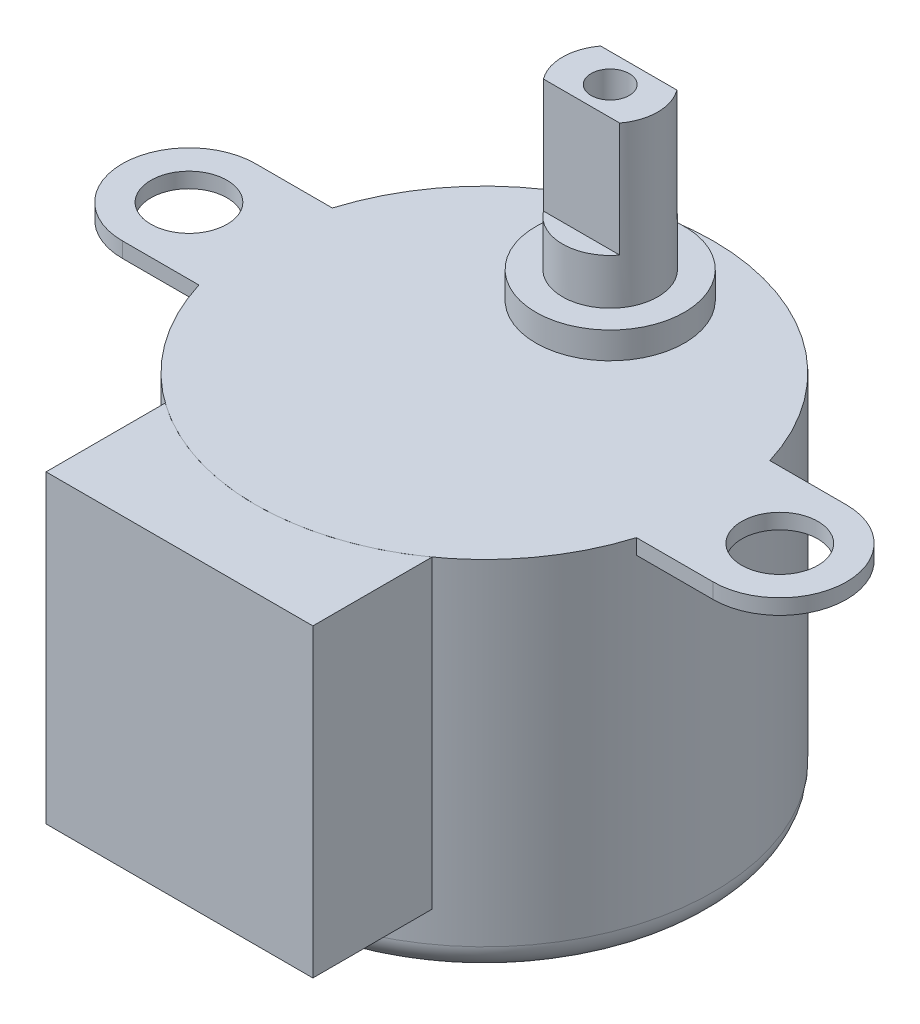
SolidWorks part; units mm, degrees
ref_plane "Front Plane" through (0, 0, 0) normal (0, 0, 1) x (1, 0, 0)
ref_plane "Top Plane" through (0, 0, 0) normal (0, 1, 0) x (1, 0, 0)
ref_plane "Right Plane" through (0, 0, 0) normal (1, 0, 0) x (0, 0, -1)
sketch "Sketch1" plane through (0, 0, 0) normal (0, 1, 0) x (1, 0, 0)
  circle A0 centre (0, 0) radius 12
  dimension "D1" = 24
extrude "Boss-Extrude1" add sketch "Sketch1" along normal blind 19
sketch "Sketch2" plane through (0, 19, 0) normal (0, 1, 0) x (1, 0, 0)
  line L1 (-7, -9.7468) -> (7, -9.7468)
  line L2 (-7, -9.7468) -> (-7, -16)
  line L3 (-7, -16) -> (7, -16)
  line L4 (7, -9.7468) -> (7, -16)
  circle A0 centre (0, 0) radius 12 construction
  point P6 (7.8636, -9.0644)
  circle M5 centre (0, 0) radius 12
  dimension "D1" = 16
  dimension "D2" = 14
extrude "Boss-Extrude2" add sketch "Sketch2" against normal blind 16 separate body contours L4 L2 L3 M5
sketch "Sketch3" plane through (0, 19, 0) normal (0, 1, 0) x (1, 0, 0)
  line L1 (-15.5, 3.5) -> (15.5, 3.5)
  line L2 (-15.5, 3.5) -> (-15.5, -3.5)
  line L3 (-15.5, -3.5) -> (15.5, -3.5)
  line L4 (15.5, 3.5) -> (15.5, -3.5)
  line L5 (-15.5, 3.5) -> (15.5, -3.5) construction
  line L6 (-15.5, -3.5) -> (15.5, 3.5) construction
  circle A0 centre (15.5, 0) radius 3.5
  circle A1 centre (-15.5, 0) radius 3.5
  point P0 (0, 0)
  circle M6 centre (0, 0) radius 12
  dimension "D1" = 7
  dimension "D2" = 31
extrude "Boss-Extrude3" add sketch "Sketch3" against normal blind 0.8 contours L2 A1 | L2 A1 | L3 L1 M6 | A1 L3 M6 | A1 L1 M6 | A0 L1 M6 | A0 L3 M6 | L4 A0 | L4 A0
sketch "Sketch4" plane through (0, 19, 0) normal (0, 1, 0) x (1, 0, 0)
  circle A0 centre (15.5, 0) radius 2
  circle A1 centre (-15.5, 0) radius 2
  dimension "D1" = 4
extrude "Cut-Extrude1" cut sketch "Sketch4" against normal through all
sketch "Sketch5" plane through (0, 19, 0) normal (0, 1, 0) x (1, 0, 0)
  line L0 (0, 0) -> (0, 12) construction
  arc A0 (11.4782, 3.5) -> (-11.4782, 3.5) centre (0, 0) ccw construction
  circle A1 centre (0, 6.6) radius 3.9
  dimension "D1" = 5.4
  dimension "D2" = 7.8
extrude "Boss-Extrude4" add sketch "Sketch5" along normal blind 1.4
sketch "Sketch6" plane through (0, 20.4, 0) normal (0, 1, 0) x (1, 0, 0)
  circle A0 centre (0, 6.6) radius 2.5
  dimension "D1" = 5
extrude "Boss-Extrude5" add sketch "Sketch6" along normal blind 8.4 separate body
sketch "Sketch7" plane through (0, 28.8, 0) normal (0, 1, 0) x (1, 0, 0)
  line L1 (-2, 8.1) -> (2, 8.1)
  line L2 (-2, 8.1) -> (-2, 5.1)
  line L3 (-2, 5.1) -> (2, 5.1)
  line L4 (2, 8.1) -> (2, 5.1)
  line L5 (-2, 8.1) -> (2, 5.1) construction
  line L6 (-2, 5.1) -> (2, 8.1) construction
  circle A1 centre (0, 6.6) radius 2.5
  circle A2 centre (0, 6.6) radius 2.5
  circle M4 centre (0, 6.6) radius 2.5
  dimension "D2" = 3
  dimension "D1" = 0
extrude "Cut-Extrude2" cut sketch "Sketch7" against normal blind 6 contours L1 M4 | L3 M4
sketch "Sketch8" plane through (0, 28.8, 0) normal (0, 1, 0) x (1, 0, 0)
  circle A0 centre (0, 6.6) radius 1
  dimension "D1" = 2
extrude "Cut-Extrude3" cut sketch "Sketch8" against normal blind 6
fillet "Fillet2" radius 1.4 1 edges at (0, 0, 12)
